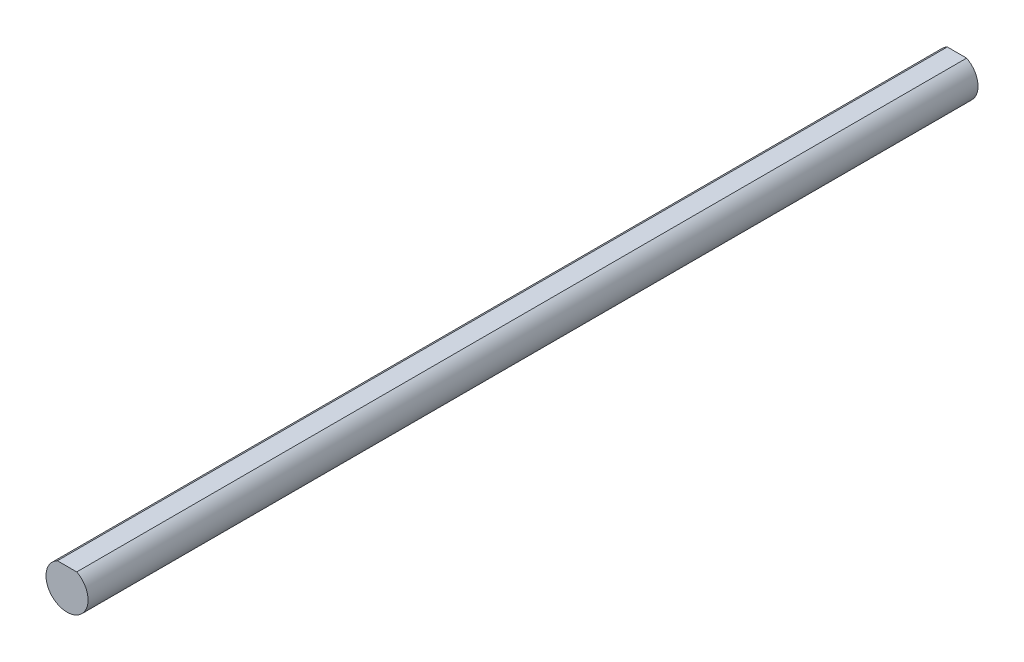
SolidWorks part; units mm, degrees
material "Alloy Steel"
ref_plane "Front Plane" through (0, 0, 0) normal (0, 0, 1) x (1, 0, 0)
ref_plane "Top Plane" through (0, 0, 0) normal (0, 1, 0) x (1, 0, 0)
ref_plane "Right Plane" through (0, 0, 0) normal (1, 0, 0) x (0, 0, -1)
sketch "Sketch1" plane through (0, 0, 0) normal (0, 0, 1) x (1, 0, 0)
  line L0 (-1.0878, 2.1) -> (1.0878, 2.1)
  arc A0 (-1.0878, 2.1) -> (1.0878, 2.1) centre (0, 0) ccw
  dimension "D1" = 4.73
  dimension "D2" = 2.1
extrude "Extrude1" add sketch "Sketch1" against normal blind 100
